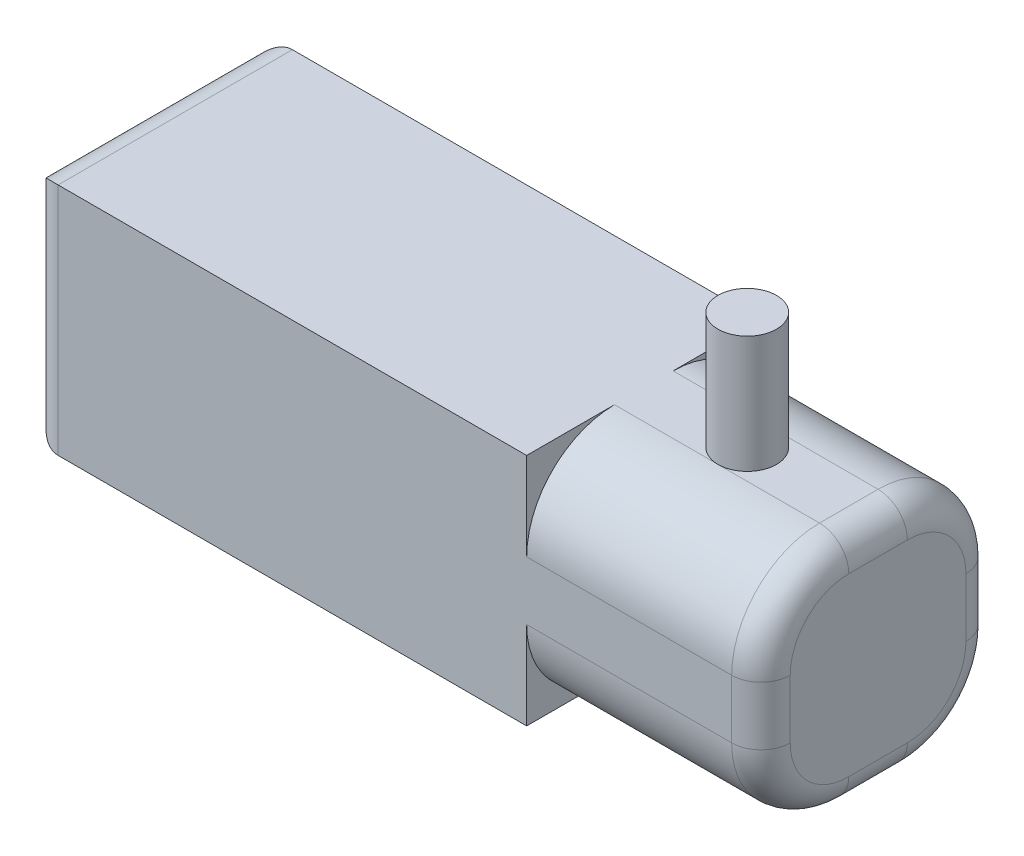
SolidWorks part; units mm, degrees
material "PVC 0.007 Plasticized"
ref_plane "Front Plane" through (0, 0, 0) normal (0, 0, 1) x (1, 0, 0)
ref_plane "Top Plane" through (0, 0, 0) normal (0, 1, 0) x (1, 0, 0)
ref_plane "Right Plane" through (0, 0, 0) normal (1, 0, 0) x (0, 0, -1)
sketch "Sketch1" plane through (0, 0, 0) normal (0, 0, 1) x (1, 0, 0)
  line L1 (-31.75, -10.16) -> (31.75, -10.16)
  line L2 (-31.75, -10.16) -> (-31.75, 10.16)
  line L3 (-31.75, 10.16) -> (31.75, 10.16)
  line L4 (31.75, -10.16) -> (31.75, 10.16)
  line L5 (-31.75, -10.16) -> (31.75, 10.16) construction
  line L6 (-31.75, 10.16) -> (31.75, -10.16) construction
  point P0 (0, 0)
  dimension "D1" = 63.5
  dimension "D2" = 20.32
extrude "Boss-Extrude1" add sketch "Sketch1" along normal blind 20.32
sketch "Sketch2" plane through (31.75, 0, 0) normal (1, 0, 0) x (0, 0, -1)
  line L4 (-20.32, 2.54) -> (-20.32, 10.16)
  line L5 (-20.32, 10.16) -> (-12.7, 10.16)
  line L6 (-7.62, 10.16) -> (0, 10.16)
  line L7 (0, 10.16) -> (0, 2.54)
  line L8 (-7.62, -10.16) -> (0, -10.16)
  line L9 (0, -10.16) -> (0, -2.54)
  line L10 (-12.7, -10.16) -> (-20.32, -10.16)
  line L11 (-20.32, -10.16) -> (-20.32, -2.54)
  arc A0 (-12.7, 10.16) -> (-20.32, 2.54) centre (-12.7, 2.54) ccw
  arc A1 (-7.62, 10.16) -> (0, 2.54) centre (-7.62, 2.54) cw
  arc A2 (-7.62, -10.16) -> (0, -2.54) centre (-7.62, -2.54) ccw
  arc A3 (-12.7, -10.16) -> (-20.32, -2.54) centre (-12.7, -2.54) cw
  point P10 (-20.32, 10.16)
  point P13 (0, 10.16)
  point P16 (0, -10.16)
  point P19 (-20.32, -10.16)
  dimension "D3" = 7.62
extrude "Cut-Extrude2" cut sketch "Sketch2" against normal blind 20.32
fillet "Fillet1" radius 2.54 8 edges at (31.75, 10.16, 10.16) (31.75, 7.9282, 18.0882) (31.75, 0, 20.32) (31.75, -7.9282, 18.0882) (31.75, -10.16, 10.16) (31.75, -7.9282, 2.2318) (31.75, 0, 0) (31.75, 7.9282, 2.2318)
sketch "Sketch3" plane through (0, 10.16, 0) normal (0, 1, 0) x (1, 0, 0)
  circle A3 centre (20.4017, -10.16) radius 2.54
extrude "Boss-Extrude2" add sketch "Sketch3" along normal blind 15.24
fillet "Fillet2" radius 2.54 4 edges at (-31.75, 10.16, 10.16) (-31.75, 0, 20.32) (-31.75, -10.16, 10.16) (-31.75, 0, 0)
sketch "Sketch4" plane through (0, 25.4, 0) normal (0, 1, 0) x (1, 0, 0)
  circle A0 centre (20.4017, -10.16) radius 2.54
extrude "Cut-Extrude3" cut sketch "Sketch4" against normal blind 5.08
